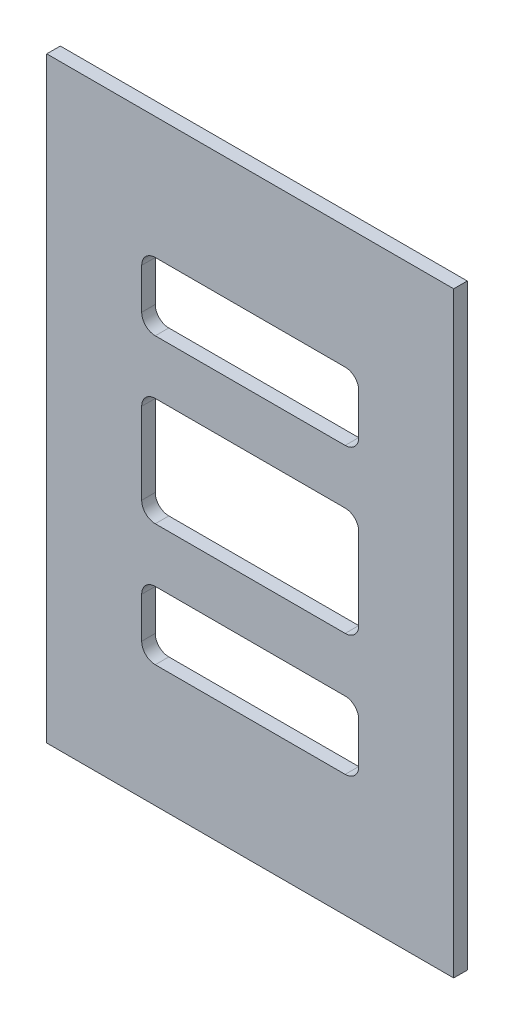
SolidWorks part; units mm, degrees
ref_plane "Front Plane" through (0, 0, 0) normal (0, 0, 1) x (1, 0, 0)
ref_plane "Top Plane" through (0, 0, 0) normal (0, 1, 0) x (1, 0, 0)
ref_plane "Right Plane" through (0, 0, 0) normal (1, 0, 0) x (0, 0, -1)
sketch "Sketch1" plane through (0, 0, 0) normal (0, 0, 1) x (1, 0, 0)
  line L1 (-15, -22) -> (15, -22)
  line L2 (-15, -22) -> (-15, 22)
  line L3 (-15, 22) -> (15, 22)
  line L4 (15, -22) -> (15, 22)
  line L5 (-15, -22) -> (15, 22) construction
  line L6 (-15, 22) -> (15, -22) construction
  line L7 (-7, 8) -> (7, 8)
  line L8 (-8, 9) -> (-8, 12)
  line L9 (-7, 13) -> (7, 13)
  line L10 (8, 9) -> (8, 12)
  line L11 (-8, 8) -> (8, 13) construction
  line L12 (-8, 13) -> (8, 8) construction
  line L13 (-7, -4) -> (7, -4)
  line L14 (-8, -3) -> (-8, 3)
  line L15 (-7, 4) -> (7, 4)
  line L16 (8, -3) -> (8, 3)
  line L17 (-8, -4) -> (8, 4) construction
  line L18 (-8, 4) -> (8, -4) construction
  line L19 (-7, -13) -> (7, -13)
  line L20 (-8, -12) -> (-8, -9)
  line L21 (-7, -8) -> (7, -8)
  line L22 (8, -12) -> (8, -9)
  line L23 (-8, -13) -> (8, -8) construction
  line L24 (-8, -8) -> (8, -13) construction
  arc A0 (-7, -13) -> (-8, -12) centre (-7, -12) cw
  arc A1 (7, -13) -> (8, -12) centre (7, -12) ccw
  arc A2 (7, -8) -> (8, -9) centre (7, -9) cw
  arc A3 (-8, -9) -> (-7, -8) centre (-7, -9) cw
  arc A4 (7, 4) -> (8, 3) centre (7, 3) cw
  arc A5 (7, -4) -> (8, -3) centre (7, -3) ccw
  arc A6 (-7, -4) -> (-8, -3) centre (-7, -3) cw
  arc A7 (-8, 3) -> (-7, 4) centre (-7, 3) cw
  arc A8 (7, 13) -> (8, 12) centre (7, 12) cw
  arc A9 (7, 8) -> (8, 9) centre (7, 9) ccw
  arc A10 (-7, 8) -> (-8, 9) centre (-7, 9) cw
  arc A11 (-8, 12) -> (-7, 13) centre (-7, 12) cw
  point P0 (0, 0)
  point P6 (0, 10.5)
  point P11 (0, 0)
  point P16 (0, -10.5)
  point P21 (0, 0)
  point P22 (0, 0)
  point P23 (8, 17.4057)
  dimension "D9" = 1
  dimension "D1" = 30
  dimension "D2" = 44
  dimension "D3" = 16
  dimension "D4" = 9
  dimension "D5" = 5
  dimension "D6" = 9
  dimension "D7" = 5
  dimension "D8" = 8
extrude "Boss-Extrude2" add sketch "Sketch1" along normal blind 1
